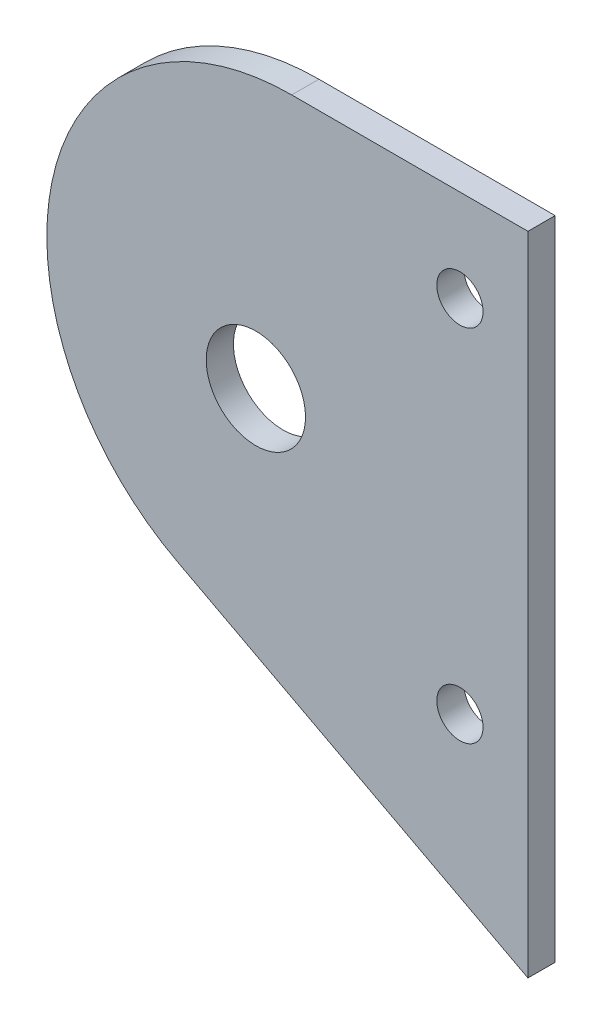
SolidWorks part; units mm, degrees
ref_plane "Plan de face" through (0, 0, 0) normal (0, 0, 1) x (1, 0, 0)
ref_plane "Plan de dessus" through (0, 0, 0) normal (0, 1, 0) x (1, 0, 0)
ref_plane "Plan de droite" through (0, 0, 0) normal (1, 0, 0) x (0, 0, -1)
sketch "Esquisse1" plane through (0, 0, 0) normal (0, 0, 1) x (1, 0, 0)
  line L0 (0, 0) -> (0, 122.747) construction
  line L1 (-175, -20) -> (175, -20) construction
  line L2 (-175, -20) -> (-175, 20) construction
  line L3 (-175, 20) -> (175, 20) construction
  line L4 (175, -20) -> (175, 20) construction
  line L5 (-175, -20) -> (175, 20) construction
  line L6 (-175, 20) -> (175, -20) construction
  line L7 (-1220, 0) -> (-110, 0) construction
  line L8 (-244.959, 40) -> (-110, 40)
  line L9 (110, 40) -> (244.959, 40)
  line L10 (110, 0) -> (110, -20) construction
  line L11 (110, -20) -> (-110, -20) construction
  line L12 (-110, 0) -> (-110, -20) construction
  line L13 (110, 0) -> (-110, -20) construction
  line L14 (110, -20) -> (-110, 0) construction
  line L15 (-244.959, 40) -> (-112.4795, -30)
  line L16 (-112.4795, -30) -> (112.4795, -30)
  line L17 (244.959, 40) -> (112.4795, -30)
  line L18 (-175, 20) -> (-58.3333, 20) construction
  line L19 (-58.3333, 20) -> (58.3333, 20) construction
  line L20 (58.3333, 20) -> (175, 20) construction
  line L21 (110, 0) -> (193.5165, 0) construction
  line L22 (110, 95) -> (-110, 95) construction
  line L23 (110, 95) -> (110, 40) construction
  line L24 (-110, 40) -> (110, 40)
  line L25 (-110, 95) -> (-110, 40) construction
  line L26 (110, 95) -> (-110, 0) construction
  line L27 (110, 0) -> (-110, 95) construction
  circle A0 centre (-175, 20) radius 3.65
  circle A1 centre (-110, -20) radius 3.65
  circle A2 centre (110, -20) radius 3.65
  circle A3 centre (175, 20) radius 3.65
  circle A4 centre (0, -20) radius 3.65
  circle A5 centre (-58.3333, 20) radius 3.65
  circle A6 centre (58.3333, 20) radius 3.65
  circle A7 centre (0, 78.03) radius 3.65 construction
  point P0 (0, 0)
  point P8 (0, -10)
  point P20 (0, 47.5)
  point P21 (0, -30)
  point P31 (0, 47.5)
  dimension "D8" = 7.3
  dimension "D10" = 58.03
  dimension "D1" = 350
  dimension "D2" = 40
  dimension "D3" = 220
  dimension "D4" = 20
  dimension "D5" = 15
  dimension "D6" = 10
  dimension "D7" = 10
  dimension "D9" = 55
extrude "Boss.-Extru.1" add sketch "Esquisse1" along normal blind 2
fillet "Congé1" radius 18 2 edges at (-244.959, 40, 1) (244.959, 40, 1)
fillet "Congé2" radius 20 2 edges at (-112.4795, -30, 1) (112.4795, -30, 1)
sketch "Esquisse2" plane through (0, 0, 0) normal (0, 0, 1) x (1, 0, 0)
  line L1 (201.7182, 61.1482) -> (-155, 61.1482)
  line L2 (201.7182, 61.1482) -> (201.7182, -35.6578)
  line L3 (201.7182, -35.6578) -> (-155, -35.6578)
  line L4 (-155, 61.1482) -> (-155, -35.6578)
  circle A0 centre (-175, 20) radius 3.65 construction
  dimension "D1" = 20
extrude "Enlèv. mat.-Extru.2" cut sketch "Esquisse2" against normal blind 10 and the other way through all
hole_wizard "Dégagement M31" positions "Esquisse4" profile "Esquisse3" hole size "M3" standard "Ansi Metric" end condition through all
sketch "Esquisse4" plane through (0, 0, 0) normal (0, 0, -1) x (-1, 0, 0)
  line L0 (160, 33.2288) -> (160, 6.7712)
  line L1 (160, 6.7712) -> (175, 10)
  line L2 (175, 20) -> (175, 10)
  circle A3 centre (175, 20) radius 10
  circle A4 centre (175, 20) radius 3.65 construction
  circle A5 centre (175, 20) radius 20
  point P0 (160, 33.2288)
  point P2 (160, 6.7712)
  dimension "D1" = 20
  dimension "D2" = 40
  dimension "D3" = 15
sketch "Esquisse3" plane through (-160, 33.2288, 0) normal (1, 0, 0) x (0, 1, 0)
  line L0 (0, 0) -> (0, 2)
  line L1 (0, 2) -> (1.7, 2)
  line L2 (1.7, 2) -> (1.7, 0)
  line L5 (1.7, 0) -> (0, 0)
  line L11 (0, -6.35) -> (0, 107.95) construction
  dimension "Diamètre du perçage jusqu'au prochain" = 3.4
  dimension "Profondeur du perçage jusqu'au prochain" = 2
